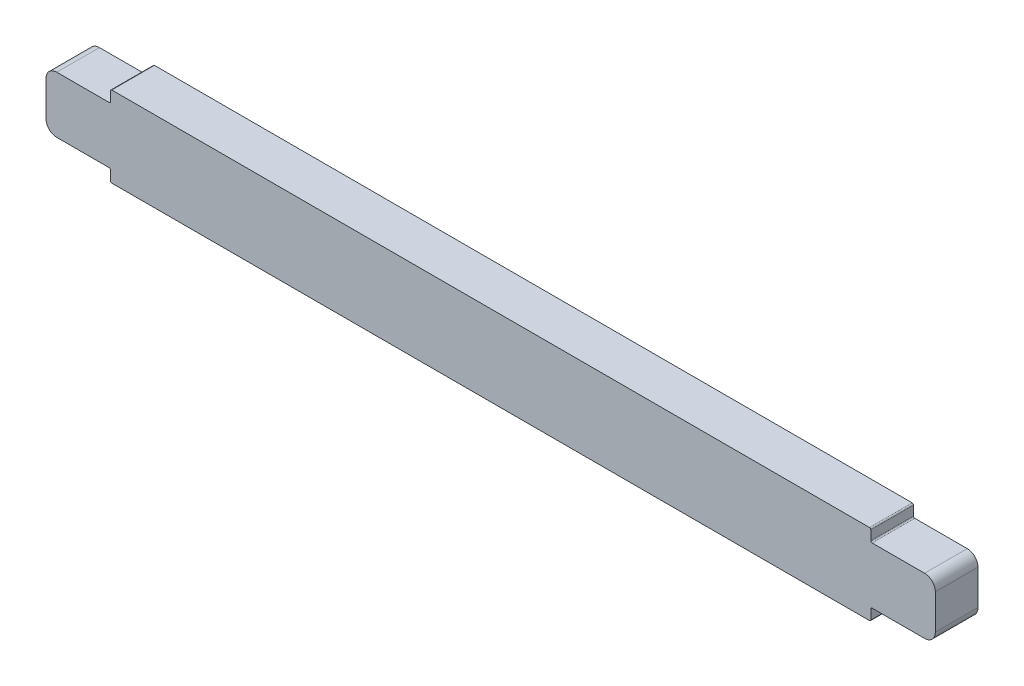
SolidWorks part; units mm, degrees
ref_plane "Front Plane" through (0, 0, 0) normal (0, 0, 1) x (1, 0, 0)
ref_plane "Top Plane" through (0, 0, 0) normal (0, 1, 0) x (1, 0, 0)
ref_plane "Right Plane" through (0, 0, 0) normal (1, 0, 0) x (0, 0, -1)
sketch "Sketch1" plane through (0, 0, 0) normal (0, 0, 1) x (1, 0, 0)
  line L1 (-33.08, -3) -> (33.08, -3)
  line L2 (-33.08, -3) -> (-33.08, 3)
  line L3 (-33.08, 3) -> (33.08, 3)
  line L4 (33.08, -3) -> (33.08, 3)
  line L5 (-33.08, -3) -> (33.08, 3) construction
  line L6 (-33.08, 3) -> (33.08, -3) construction
  point P0 (0, 0)
  dimension "D1" = 66.16
  dimension "D2" = 6
extrude "Boss-Extrude1" add sketch "Sketch1" along normal blind 3.175
sketch "Sketch3" plane through (0, 0, 3.175) normal (0, 0, 1) x (1, 0, 0)
  line L0 (-28.28, -2.1) -> (-28.28, 2.1) construction
  line L1 (-33.08, 3) -> (-28.28, 3)
  line L2 (-33.08, 3) -> (-33.08, 2.1)
  line L3 (-33.08, 2.1) -> (-28.28, 2.1)
  line L4 (-28.28, 3) -> (-28.28, 2.1)
  line L5 (-33.08, -3) -> (-28.28, -3)
  line L6 (-33.08, -3) -> (-33.08, -2.1)
  line L7 (-33.08, -2.1) -> (-28.28, -2.1)
  line L8 (-28.28, -3) -> (-28.28, -2.1)
  line L9 (-33.08, 0) -> (-28.28, 0) construction
  line L10 (-33.08, 3) -> (-33.08, -3) construction
  dimension "D1" = 4.2
  dimension "D2" = 4.8
extrude "Cut-Extrude1" cut sketch "Sketch3" against normal through all
mirror "Mirror1" about plane through (0, 0, 0) normal (1, 0, 0) of "Cut-Extrude1"
fillet "Fillet1" radius 0.8 4 edges at (33.08, 2.1, 1.5875) (33.08, -2.1, 1.5875) (-33.08, 2.1, 1.5875) (-33.08, -2.1, 1.5875)
fillet "Fillet2" radius 0.1 8 edges at (28.28, 2.1, 1.5875) (28.28, 3, 1.5875) (-28.28, 3, 1.5875) (-28.28, 2.1, 1.5875) (-28.28, -3, 1.5875) (28.28, -3, 1.5875) (28.28, -2.1, 1.5875) (-28.28, -2.1, 1.5875)
